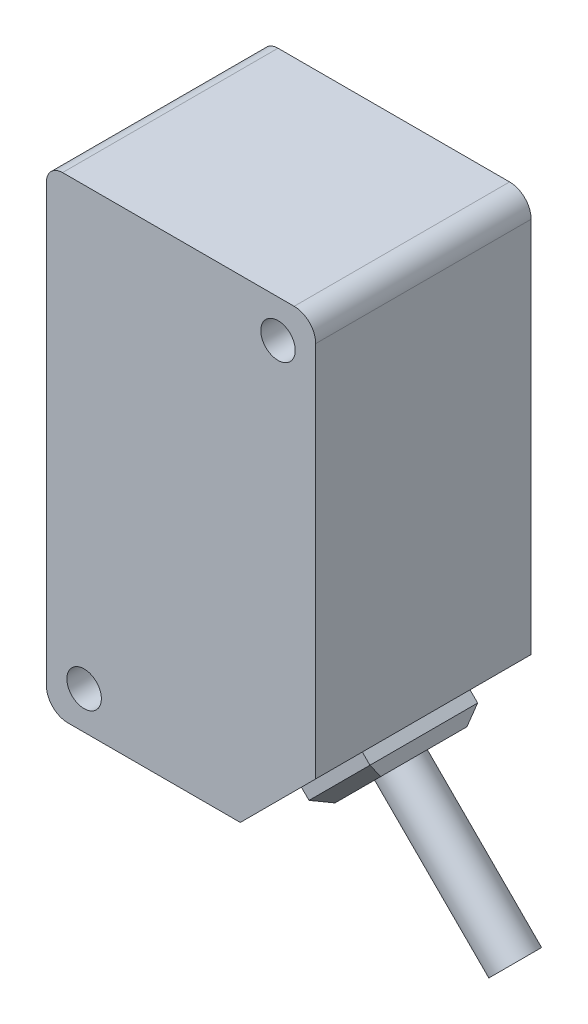
SolidWorks part; units mm, degrees
ref_plane "前视基准面" through (0, 0, 0) normal (0, 0, 1) x (1, 0, 0)
ref_plane "上视基准面" through (0, 0, 0) normal (0, 1, 0) x (1, 0, 0)
ref_plane "右视基准面" through (0, 0, 0) normal (1, 0, 0) x (0, 0, -1)
sketch "草图1" plane through (0, 0, 0) normal (0, 0, 1) x (1, 0, 0)
  line L0 (21.5, 40.5) -> (21.5, 3.5) construction
  line L1 (0, 0) -> (25, 0) construction
  line L2 (0, 0) -> (0, 44)
  line L3 (0, 44) -> (25, 44)
  line L4 (25, 7) -> (25, 44)
  line L5 (21.5, 3.5) -> (3.5, 3.5) construction
  line L6 (18, 0) -> (25, 7)
  line L7 (0, 0) -> (18, 0)
  circle A0 centre (21.5, 40.5) radius 1.6
  circle A1 centre (3.5, 3.5) radius 1.6
  point P12 (21.5, 3.5)
  dimension "D3" = 3.2
  dimension "D7" = 3.2
  dimension "D8" = 3.5
  dimension "D1" = 25
  dimension "D2" = 44
  dimension "D4" = 3.5
  dimension "D5" = 3.5
  dimension "D6" = 3.5
extrude "凸台-拉伸1" add sketch "草图1" along normal blind 20
sketch "草图2" plane through (0, 0, 0) normal (-1, 0, 0) x (0, 0, 1)
  line L0 (20, 44) -> (0, 44) construction
  line L1 (20, 44) -> (20, 0) construction
  circle A0 centre (10, 37.7) radius 1.6
  point P4 (0, 0)
  dimension "D2" = 3.2
  dimension "D1" = 6.3
  dimension "D3" = 10
extrude "切除-拉伸1" cut sketch "草图2" against normal blind 1
fillet "圆角1" radius 1.5 1 edges at (0, 44, 10)
fillet "圆角2" radius 2 2 edges at (0, 0, 10) (25, 44, 10)
sketch "草图3" plane through (9, -9, 0) normal (0.7071, -0.7071, 0) x (0, 0, -1)
  line L0 (-10, 12.7279) -> (-10, 22.6274) construction
  line L1 (-20, 12.7279) -> (0, 12.7279) construction
  line L2 (-20, 22.6274) -> (0, 22.6274) construction
  line L3 (-20, 17.6777) -> (0, 17.6777) construction
  line L4 (-20, 12.7279) -> (-20, 22.6274) construction
  line L5 (0, 12.7279) -> (0, 22.6274) construction
  line L7 (-15, 21.6777) -> (-5, 21.6777)
  line L8 (-15, 21.6777) -> (-15, 13.6777)
  line L9 (-15, 13.6777) -> (-5, 13.6777)
  line L10 (-5, 21.6777) -> (-5, 13.6777)
  line L11 (-15, 21.6777) -> (-5, 13.6777) construction
  line L12 (-15, 13.6777) -> (-5, 21.6777) construction
  point P12 (-10, 17.6777)
  dimension "D1" = 8
  dimension "D2" = 10
extrude "凸台-拉伸2" add sketch "草图3" along normal blind 2
chamfer "倒角1" distance 1 angle 45 4 edges at (22.9142, 2.0858, 5) (20.0858, -0.7426, 10) (22.9142, 2.0858, 15) (25.7426, 4.9142, 10)
sketch "草图4" plane through (10.4142, -10.4142, 0) normal (0.7071, -0.7071, 0) x (0, 0, -1)
  circle A0 centre (-10, 17.6777) radius 2
  dimension "D1" = 4
extrude "凸台-拉伸3" add sketch "草图4" along normal blind 15
